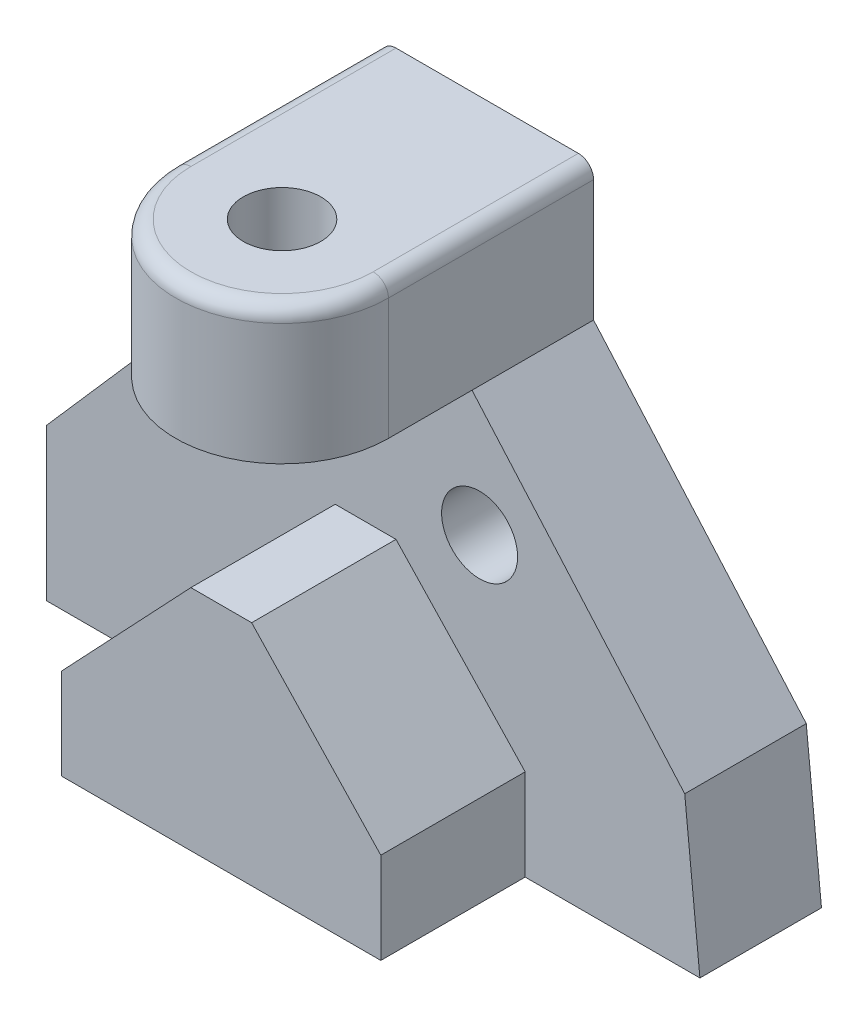
SolidWorks part; units mm, degrees
ref_plane "Front" through (0, 0, 0) normal (0, 0, 1) x (1, 0, 0)
ref_plane "Top" through (0, 0, 0) normal (0, 1, 0) x (1, 0, 0)
ref_plane "Right" through (0, 0, 0) normal (1, 0, 0) x (0, 0, -1)
sketch "草图1" plane through (0, 0, 0) normal (0, 0, 1) x (1, 0, 0)
  line L0 (14, 32) -> (-14, 32)
  line L1 (-14, 32) -> (-42, 0)
  line L2 (-42, 0) -> (-42, -20)
  line L3 (-42, -20) -> (44, -20)
  line L5 (42, 0) -> (44, -20)
  line L6 (14, 32) -> (42, 0)
  point P0 (0, 32)
  dimension "D1" = 28
  dimension "D2" = 20
  dimension "D3" = 86
  dimension "D4" = 52
extrude "凸台-拉伸1" add sketch "草图1" along normal blind 16
sketch "草图2" plane through (0, 0, 16) normal (0, 0, 1) x (1, 0, 0)
  line L0 (4, 10) -> (-4, 10)
  line L1 (-4, 10) -> (-21, -8)
  line L2 (-21, -8) -> (-21, -20)
  line L3 (-42, -20) -> (44, -20) construction
  line L4 (-21, -20) -> (21, -20)
  line L6 (21, -8) -> (21, -20)
  line L7 (4, 10) -> (21, -8)
  dimension "D1" = 30
  dimension "D2" = 12
  dimension "D3" = 8
  dimension "D4" = 42
extrude "凸台-拉伸2" add sketch "草图2" along normal blind 19 contours L1 L2 L4 L6 L7 L0
sketch "草图5" plane through (0, 32, 0) normal (0, 1, 0) x (1, 0, 0)
  line L0 (14, -16) -> (-14, -16) construction
  line L5 (-14, 0) -> (-42, 0) construction
  line L6 (-14, -27) -> (14, -27)
  line L7 (-14, -27) -> (-14, 0)
  line L8 (-14, 0) -> (14, 0)
  line L9 (14, -27) -> (14, 0)
  line L10 (-14, -27) -> (14, 0) construction
  line L11 (-14, 0) -> (14, -27) construction
  line L12 (14, 0) -> (-14, 0) construction
  arc A0 (-14, -27) -> (14, -27) centre (0, -27) ccw
  point P0 (0, -13.5)
  point P11 (0, 0)
  point P14 (0, -16)
  dimension "D2" = 14
  dimension "D1" = 27
extrude "凸台-拉伸3" add sketch "草图5" along normal blind 18 contours L6 A0
fillet "圆角1" radius 2 3 edges at (14, 50, 13.5) (0, 50, 41) (-14, 50, 13.5)
hole_wizard "M12 螺纹孔1" positions "草图8" profile "草图9" tap size "M12" standard "GB"
sketch "草图8" plane through (0, 50, 0) normal (0, 1, 0) x (1, 0, 0)
  line L6 (12, -27) -> (12, 0)
  line L7 (12, 0) -> (-12, 0)
  line L8 (-12, 0) -> (-12, -27)
  line L9 (12, -27) -> (12, 0)
  line L10 (12, 0) -> (-12, 0)
  line L11 (-12, 0) -> (-12, -27)
  arc A2 (-12, -27) -> (12, -27) centre (0, -27) ccw
  arc A3 (-12, -27) -> (12, -27) centre (0, -27) ccw
  point P19 (0, -27)
  dimension "D1" = 0
sketch "草图9" plane through (0, 50, 27) normal (1, 0, 0) x (0, 0, 1)
  line L0 (0, 0) -> (0, 18)
  line L1 (0, 18) -> (5.1, 18)
  line L2 (5.1, 18) -> (5.1, 0)
  line L5 (5.1, 0) -> (0, 0)
  line L11 (0, -6.35) -> (0, 107.95) construction
  dimension "通孔螺纹孔钻头直径" = 10.2
  dimension "通孔螺纹孔钻头深度" = 18
cosmetic thread "孔螺蚊线1" parameters "D2"=12
hole_wizard "Ø10.0 (10) 直径孔1" positions "草图10" profile "草图11" hole size "Ø10.0" standard "GB" end condition through all
sketch "草图10" plane through (0, 0, 16) normal (0, 0, 1) x (1, 0, 0)
  line L0 (0, 0) -> (0, 35.6549) construction
  line L2 (-42, -20) -> (-21, -20) construction
  point P0 (-15, 16)
  point P2 (15, 16)
  point P11 (0, 0)
  point P16 (-8.328, 6.9601)
  point P21 (-13.0364, 8.6481)
  dimension "D1" = 30
  dimension "D2" = 36
sketch "草图11" plane through (-15, 16, 16) normal (1, 0, 0) x (0, -1, 0)
  line L0 (0, 0) -> (0, 16)
  line L1 (0, 16) -> (5, 16)
  line L2 (5, 16) -> (5, 0)
  line L5 (5, 0) -> (0, 0)
  line L11 (0, -6.35) -> (0, 107.95) construction
  dimension "通孔孔直径" = 10
  dimension "通孔孔深度" = 16
